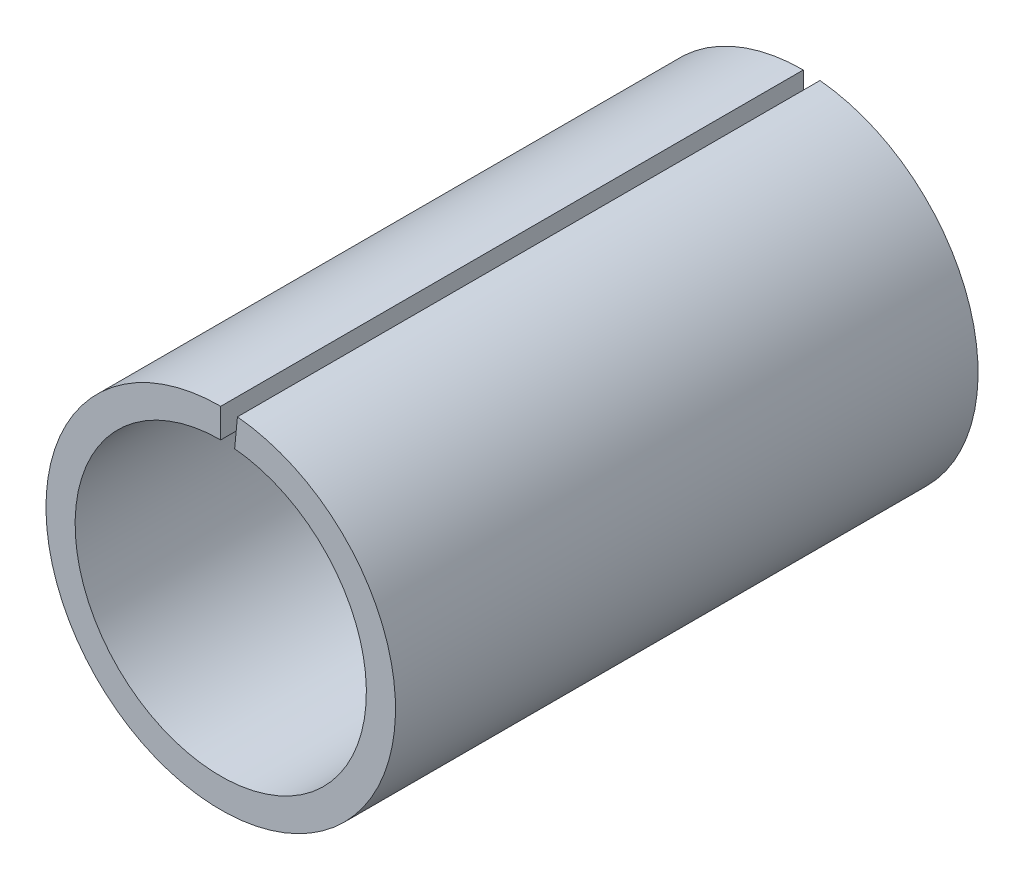
SolidWorks part; units mm, degrees
ref_plane "前视基准面" through (0, 0, 0) normal (0, 0, 1) x (1, 0, 0)
ref_plane "上视基准面" through (0, 0, 0) normal (0, 1, 0) x (1, 0, 0)
ref_plane "右视基准面" through (0, 0, 0) normal (1, 0, 0) x (0, 0, -1)
sketch "草图1" plane through (0, 0, 0) normal (0, 0, 1) x (1, 0, 0)
  circle A0 centre (0, 0) radius 6
  circle A1 centre (0, 0) radius 5
  dimension "D1" = 10
  dimension "D2" = 12
extrude "凸台-拉伸1" add sketch "草图1" along normal blind 20
sketch "草图2" plane through (0, 0, 20) normal (0, 0, 1) x (1, 0, 0)
  line L0 (0, 0) -> (0, 12.6809)
  line L1 (0, 0) -> (1.2166, 12.6809)
  line L2 (1.2166, 12.6809) -> (0, 12.6809)
extrude "切除-拉伸1" cut sketch "草图2" against normal blind 100
